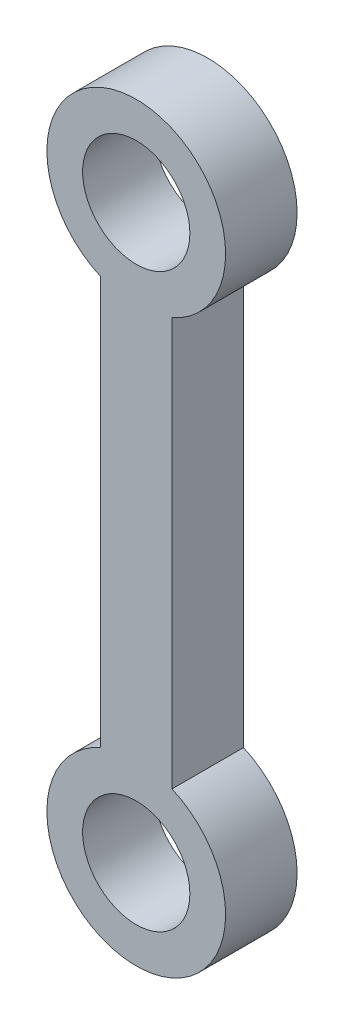
SolidWorks part; units mm, degrees
ref_plane "Front Plane" through (0, 0, 0) normal (0, 0, 1) x (1, 0, 0)
ref_plane "Top Plane" through (0, 0, 0) normal (0, 1, 0) x (1, 0, 0)
ref_plane "Right Plane" through (0, 0, 0) normal (1, 0, 0) x (0, 0, -1)
sketch "Sketch1" plane through (0, 0, 0) normal (0, 0, 1) x (1, 0, 0)
  line L0 (0, 0) -> (0, 51.1406) construction
  line L1 (-5, 80) -> (5, 80)
  line L2 (-5, 80) -> (-5, 0)
  line L3 (-5, 0) -> (5, 0)
  line L4 (5, 80) -> (5, 0)
  circle A0 centre (0, 0) radius 12.5
  circle A1 centre (0, 80) radius 12.5
  circle A2 centre (0, 80) radius 7.5
  circle A3 centre (0, 0) radius 7.5
  dimension "D3" = 25
  dimension "D4" = 15
  dimension "D5" = 15
  dimension "D1" = 10
  dimension "D2" = 80
extrude "Boss-Extrude1" add sketch "Sketch1" along normal blind 10
